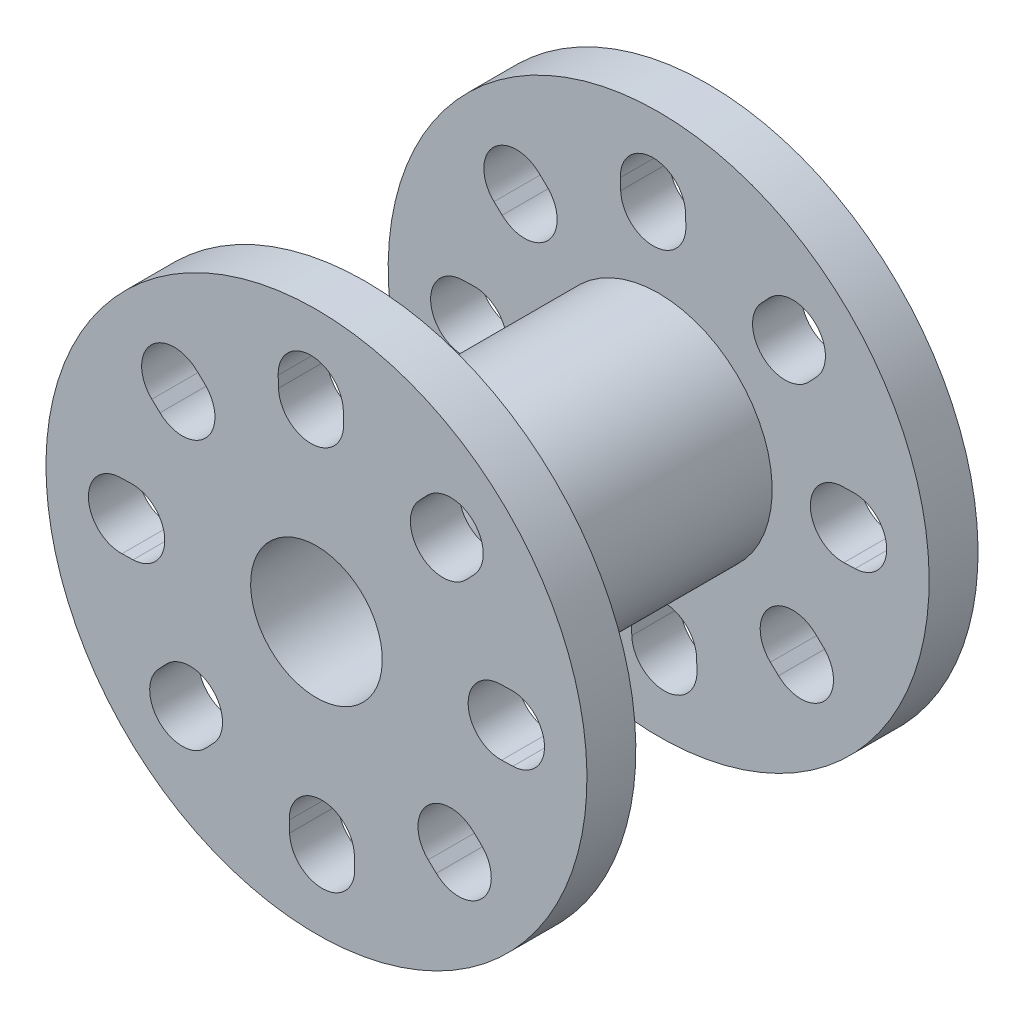
SolidWorks part; units mm, degrees
ref_plane "前视基准面" through (0, 0, 0) normal (0, 0, 1) x (1, 0, 0)
ref_plane "上视基准面" through (0, 0, 0) normal (0, 1, 0) x (1, 0, 0)
ref_plane "右视基准面" through (0, 0, 0) normal (1, 0, 0) x (0, 0, -1)
other "Configuration Table"
sketch "草图4" plane through (0, 0, -1.4) normal (0, 0, -1) x (-1, 0, 0)
  line L1 (-6.7794, 10.1015) -> (-6.3085, 9.6023) construction
  line L2 (-9.2182, 6.8575) -> (-9.6891, 7.3567) construction
  line L3 (-6.7794, 10.1015) -> (-6.3085, 9.6023)
  line L4 (-9.2182, 6.8575) -> (-9.6891, 7.3567)
  line L5 (-1.6692, 11.3672) -> (-1.6492, 12.0532)
  line L6 (2.3491, 11.9366) -> (2.3291, 11.2506)
  line L7 (6.8575, 9.2182) -> (7.3567, 9.6891)
  line L8 (10.1015, 6.7794) -> (9.6023, 6.3085)
  line L9 (11.3672, 1.6692) -> (12.0532, 1.6492)
  line L10 (11.9366, -2.3491) -> (11.2506, -2.3291)
  line L11 (9.2182, -6.8575) -> (9.6891, -7.3567)
  line L12 (6.7794, -10.1015) -> (6.3085, -9.6023)
  line L13 (1.6692, -11.3672) -> (1.6492, -12.0532)
  line L14 (-2.3491, -11.9366) -> (-2.3291, -11.2506)
  line L15 (-6.8575, -9.2182) -> (-7.3567, -9.6891)
  line L16 (-10.1015, -6.7794) -> (-9.6023, -6.3085)
  line L17 (-11.3672, -1.6692) -> (-12.0532, -1.6492)
  line L18 (-11.9366, 2.3491) -> (-11.2506, 2.3291)
  circle A0 centre (0, 0) radius 16.6
  circle A1 centre (0, 0) radius 4.04
  arc A2 (-9.6066, 10.184) -> (-9.6891, 7.3567) centre (-8.2342, 8.7291) ccw construction
  arc A3 (-6.7794, 10.1015) -> (-9.6066, 10.184) centre (-8.2342, 8.7291) ccw construction
  arc A4 (-9.2182, 6.8575) -> (-6.3085, 9.6023) centre (-7.7633, 8.2299) ccw construction
  arc A5 (-9.6066, 10.184) -> (-9.6891, 7.3567) centre (-8.2342, 8.7291) ccw
  arc A6 (-6.7794, 10.1015) -> (-9.6066, 10.184) centre (-8.2342, 8.7291) ccw
  arc A7 (-9.2182, 6.8575) -> (-6.3085, 9.6023) centre (-7.7633, 8.2299) ccw
  arc A8 (-1.6692, 11.3672) -> (2.3291, 11.2506) centre (0.3299, 11.3089) ccw
  arc A9 (0.4083, 13.994) -> (-1.6492, 12.0532) centre (0.3499, 11.9949) ccw
  arc A10 (2.3491, 11.9366) -> (0.4083, 13.994) centre (0.3499, 11.9949) ccw
  arc A11 (6.8575, 9.2182) -> (9.6023, 6.3085) centre (8.2299, 7.7633) ccw
  arc A12 (10.184, 9.6066) -> (7.3567, 9.6891) centre (8.7291, 8.2342) ccw
  arc A13 (10.1015, 6.7794) -> (10.184, 9.6066) centre (8.7291, 8.2342) ccw
  arc A14 (11.3672, 1.6692) -> (11.2506, -2.3291) centre (11.3089, -0.3299) ccw
  arc A15 (13.994, -0.4083) -> (12.0532, 1.6492) centre (11.9949, -0.3499) ccw
  arc A16 (11.9366, -2.3491) -> (13.994, -0.4083) centre (11.9949, -0.3499) ccw
  arc A17 (9.2182, -6.8575) -> (6.3085, -9.6023) centre (7.7633, -8.2299) ccw
  arc A18 (9.6066, -10.184) -> (9.6891, -7.3567) centre (8.2342, -8.7291) ccw
  arc A19 (6.7794, -10.1015) -> (9.6066, -10.184) centre (8.2342, -8.7291) ccw
  arc A20 (1.6692, -11.3672) -> (-2.3291, -11.2506) centre (-0.3299, -11.3089) ccw
  arc A21 (-0.4083, -13.994) -> (1.6492, -12.0532) centre (-0.3499, -11.9949) ccw
  arc A22 (-2.3491, -11.9366) -> (-0.4083, -13.994) centre (-0.3499, -11.9949) ccw
  arc A23 (-6.8575, -9.2182) -> (-9.6023, -6.3085) centre (-8.2299, -7.7633) ccw
  arc A24 (-10.184, -9.6066) -> (-7.3567, -9.6891) centre (-8.7291, -8.2342) ccw
  arc A25 (-10.1015, -6.7794) -> (-10.184, -9.6066) centre (-8.7291, -8.2342) ccw
  arc A26 (-11.3672, -1.6692) -> (-11.2506, 2.3291) centre (-11.3089, 0.3299) ccw
  arc A27 (-13.994, 0.4083) -> (-12.0532, -1.6492) centre (-11.9949, 0.3499) ccw
  arc A28 (-11.9366, 2.3491) -> (-13.994, 0.4083) centre (-11.9949, 0.3499) ccw
  point P63 (0, 0)
  dimension "D1" = 33.2
  dimension "D2" = 8.08
extrude "凸台-拉伸1" add sketch "草图4" along normal blind 3
sketch "草图5" plane through (0, 0, -4.4) normal (0, 0, -1) x (-1, 0, 0)
  circle A0 centre (0, 0) radius 6.9656
  circle A1 centre (0, 0) radius 4.04
  dimension "D1" = 8.08
extrude "凸台-拉伸2" add sketch "草图5" along normal blind 18
sketch "草图8" plane through (0, 0, -22.4) normal (0, 0, -1) x (-1, 0, 0)
  line L32 (-2.3291, -11.2506) -> (-2.3491, -11.9366) construction
  line L33 (1.6492, -12.0532) -> (1.6692, -11.3672) construction
  line L34 (-2.3291, -11.2506) -> (-2.3491, -11.9366)
  line L35 (1.6492, -12.0532) -> (1.6692, -11.3672)
  line L36 (-9.6023, -6.3085) -> (-10.1015, -6.7794)
  line L37 (-7.3567, -9.6891) -> (-6.8575, -9.2182)
  line L38 (-11.2506, 2.3291) -> (-11.9366, 2.3491)
  line L39 (-12.0532, -1.6492) -> (-11.3672, -1.6692)
  line L40 (-6.3085, 9.6023) -> (-6.7794, 10.1015)
  line L41 (-9.6891, 7.3567) -> (-9.2182, 6.8575)
  line L42 (2.3291, 11.2506) -> (2.3491, 11.9366)
  line L43 (-1.6492, 12.0532) -> (-1.6692, 11.3672)
  line L44 (9.6023, 6.3085) -> (10.1015, 6.7794)
  line L45 (7.3567, 9.6891) -> (6.8575, 9.2182)
  line L46 (11.2506, -2.3291) -> (11.9366, -2.3491)
  line L47 (12.0532, 1.6492) -> (11.3672, 1.6692)
  line L48 (6.3085, -9.6023) -> (6.7794, -10.1015)
  line L49 (9.6891, -7.3567) -> (9.2182, -6.8575)
  circle A0 centre (0, 0) radius 16.6
  arc A32 (1.6692, -11.3672) -> (-2.3291, -11.2506) centre (-0.3299, -11.3089) ccw construction
  arc A33 (-2.3491, -11.9366) -> (1.6492, -12.0532) centre (-0.3499, -11.9949) ccw construction
  arc A34 (1.6692, -11.3672) -> (-2.3291, -11.2506) centre (-0.3299, -11.3089) ccw
  arc A35 (-2.3491, -11.9366) -> (1.6492, -12.0532) centre (-0.3499, -11.9949) ccw
  arc A36 (-10.1015, -6.7794) -> (-7.3567, -9.6891) centre (-8.7291, -8.2342) ccw
  arc A37 (-6.8575, -9.2182) -> (-9.6023, -6.3085) centre (-8.2299, -7.7633) ccw
  arc A38 (-11.9366, 2.3491) -> (-12.0532, -1.6492) centre (-11.9949, 0.3499) ccw
  arc A39 (-11.3672, -1.6692) -> (-11.2506, 2.3291) centre (-11.3089, 0.3299) ccw
  arc A40 (-6.7794, 10.1015) -> (-9.6891, 7.3567) centre (-8.2342, 8.7291) ccw
  arc A41 (-9.2182, 6.8575) -> (-6.3085, 9.6023) centre (-7.7633, 8.2299) ccw
  arc A42 (2.3491, 11.9366) -> (-1.6492, 12.0532) centre (0.3499, 11.9949) ccw
  arc A43 (-1.6692, 11.3672) -> (2.3291, 11.2506) centre (0.3299, 11.3089) ccw
  arc A44 (10.1015, 6.7794) -> (7.3567, 9.6891) centre (8.7291, 8.2342) ccw
  arc A45 (6.8575, 9.2182) -> (9.6023, 6.3085) centre (8.2299, 7.7633) ccw
  arc A46 (11.9366, -2.3491) -> (12.0532, 1.6492) centre (11.9949, -0.3499) ccw
  arc A47 (11.3672, 1.6692) -> (11.2506, -2.3291) centre (11.3089, -0.3299) ccw
  arc A48 (6.7794, -10.1015) -> (9.6891, -7.3567) centre (8.2342, -8.7291) ccw
  arc A49 (9.2182, -6.8575) -> (6.3085, -9.6023) centre (7.7633, -8.2299) ccw
  circle A50 centre (0, 0) radius 4.04
  point P54 (0, 0)
extrude "凸台-拉伸3" add sketch "草图8" along normal blind 3 separate body
